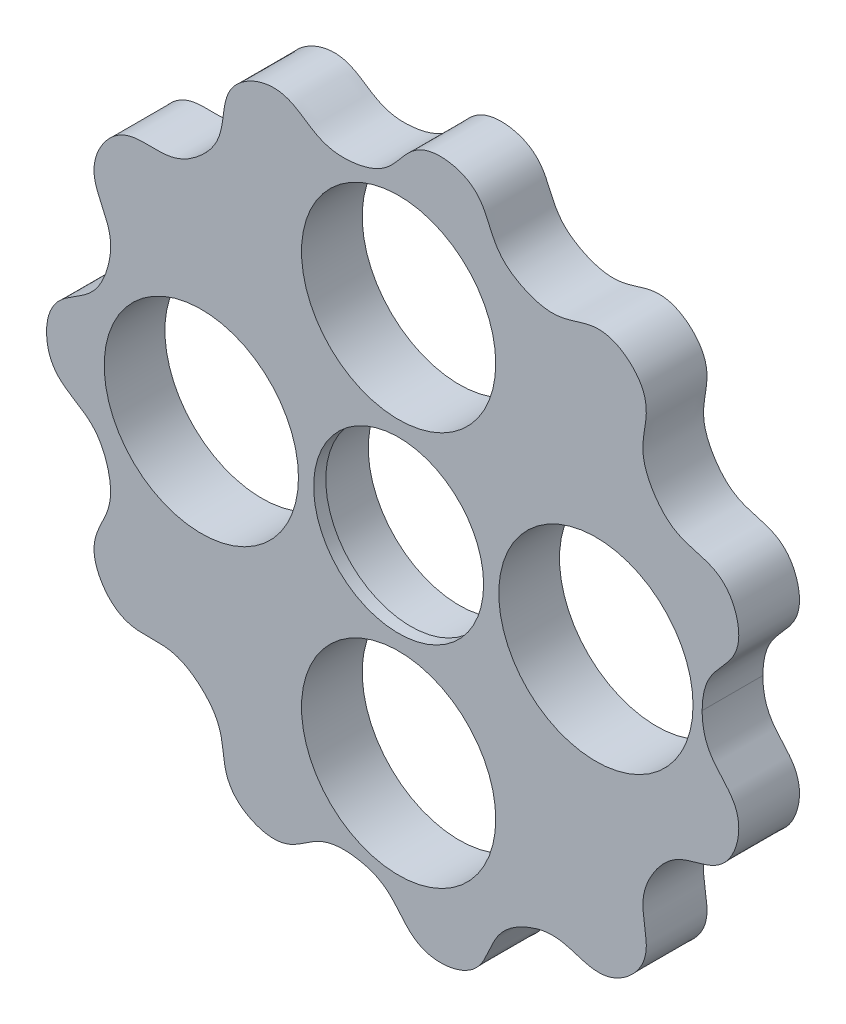
SolidWorks part; units mm, degrees
material "ABS"
ref_plane "Front Plane" through (0, 0, 0) normal (0, 0, 1) x (1, 0, 0)
ref_plane "Top Plane" through (0, 0, 0) normal (0, 1, 0) x (1, 0, 0)
ref_plane "Right Plane" through (0, 0, 0) normal (1, 0, 0) x (0, 0, -1)
sketch "Sketch2" plane through (0, 0, 0) normal (0, 0, 1) x (1, 0, 0)
  line L0 (2, 0) -> (18.25, 0) construction
  line L1 (2, 0) -> (2, 16.25) construction
  line L2 (2, 0) -> (-14.25, 0) construction
  line L3 (2, 0) -> (2, -16.25) construction
  circle A0 centre (2, 0) radius 7.5
  circle A1 centre (18.25, 0) radius 8
  circle A2 centre (2, 16.25) radius 8
  circle A3 centre (-14.25, 0) radius 8
  circle A4 centre (2, -16.25) radius 8
  spline S0 degree 5 poles (-27, 0) (-27, -0.3812) (-26.9508, -0.8895) (-26.8075, -1.5014) (-26.5012, -2.1537) (-25.894, -2.8636) (-25.332, -3.3018) (-24.7079, -3.6802) (-23.8757, -4.1833) (-23.0502, -4.8561) (-22.3649, -5.8294) (-21.9277, -7.0292) (-21.6821, -8.2633) (-21.7019, -9.3372) (-21.9494, -10.2468) (-22.241, -10.9072) (-22.5702, -11.5609) (-22.8569, -12.2233) (-23.03, -12.7873) (-23.1411, -13.5971) (-23.0145, -14.5495) (-22.5942, -15.4953) (-21.9781, -16.3412) (-21.2192, -16.9653) (-20.5887, -17.288) (-19.9177, -17.4897) (-19.208, -17.5545) (-18.4785, -17.5354) (-17.5064, -17.5087) (-16.4482, -17.6284) (-15.3454, -18.0767) (-14.3289, -18.8496) (-13.4551, -19.755) (-12.8912, -20.6692) (-12.6077, -21.5682) (-12.496, -22.2814) (-12.4195, -23.0093) (-12.3025, -23.7215) (-12.1433, -24.2896) (-11.7989, -25.0309) (-11.1775, -25.7637) (-10.3126, -26.3321) (-9.3369, -26.7106) (-8.3611, -26.8254) (-7.6562, -26.7559) (-6.9827, -26.5629) (-6.3507, -26.2337) (-5.7472, -25.8232) (-4.9439, -25.2752) (-3.989, -24.8038) (-2.8189, -24.5847) (-1.5459, -24.6854) (-0.3213, -24.9747) (0.6473, -25.4388) (1.3719, -26.0418) (1.8515, -26.5814) (2.3093, -27.1524) (2.7928, -27.6883) (3.2339, -28.0801) (3.9243, -28.5176) (4.8433, -28.7981) (5.8782, -28.8087) (6.9036, -28.5996) (7.7866, -28.1686) (8.342, -27.7291) (8.8042, -27.2025) (9.158, -26.5839) (9.4437, -25.9123) (9.8233, -25.017) (10.3717, -24.1041) (11.2376, -23.2873) (12.3629, -22.6837) (13.5495, -22.265) (14.6153, -22.1318) (15.5508, -22.2474) (16.2461, -22.442) (16.9399, -22.6749) (17.6364, -22.8643) (18.2193, -22.9554) (19.0366, -22.9502) (19.9613, -22.6893) (20.8377, -22.1387) (21.5873, -21.4084) (22.0971, -20.5685) (22.3267, -19.8984) (22.4309, -19.2056) (22.394, -18.4939) (22.2713, -17.7745) (22.1066, -16.8161) (22.0744, -15.7516) (22.3612, -14.5963) (22.9816, -13.4802) (23.7534, -12.4864) (24.578, -11.7981) (25.4275, -11.3895) (26.1176, -11.1774) (26.8272, -10.9982) (27.5155, -10.781) (28.0551, -10.5425) (28.7399, -10.0962) (29.3768, -9.3768) (29.8163, -8.4398) (30.0522, -7.4202) (30.0269, -6.438) (29.8578, -5.7502) (29.5709, -5.111) (29.1551, -4.5322) (28.6629, -3.9934) (28.0062, -3.2762) (27.4036, -2.3981) (27.1353, -1.6092) (27.026, -0.874) (27, -0.2497) (27, 0) knots 0.5 0.5 0.5 0.5 0.5 0.5 0.509091 0.512121 0.515152 0.518182 0.524242 0.527273 0.530303 0.539394 0.545455 0.554545 0.557576 0.560606 0.566667 0.569697 0.572727 0.575758 0.578788 0.581818 0.590909 0.59697 0.6 0.60303 0.606061 0.609091 0.615152 0.618182 0.621212 0.630303 0.636364 0.645455 0.648485 0.651515 0.657576 0.660606 0.663636 0.666667 0.669697 0.672727 0.681818 0.687879 0.690909 0.693939 0.69697 0.7 0.706061 0.709091 0.712121 0.721212 0.727273 0.736364 0.739394 0.742424 0.748485 0.751515 0.754545 0.757576 0.760606 0.763636 0.772727 0.778788 0.781818 0.784848 0.787879 0.790909 0.79697 0.8 0.80303 0.812121 0.818182 0.827273 0.830303 0.833333 0.839394 0.842424 0.845455 0.848485 0.851515 0.854545 0.863636 0.869697 0.872727 0.875758 0.878788 0.881818 0.887879 0.890909 0.893939 0.90303 0.909091 0.918182 0.921212 0.924242 0.930303 0.933333 0.936364 0.939394 0.942424 0.945455 0.954545 0.960606 0.963636 0.966667 0.969697 0.972727 0.978788 0.981818 0.984848 0.993939 1 1 1 1 1 1 weights 1 1 1 1 1 1 1 1 1 1 1 1 1 1 1 1 1 1 1 1 1 1 1 1 1 1 1 1 1 1 1 1 1 1 1 1 1 1 1 1 1 1 1 1 1 1 1 1 1 1 1 1 1 1 1 1 1 1 1 1 1 1 1 1 1 1 1 1 1 1 1 1 1 1 1 1 1 1 1 1 1 1 1 1 1 1 1 1 1 1 1 1 1 1 1 1 1 1 1 1 1 1 1 1 1 1 1 1 1 1 1 1 1 1
  spline S1 degree 5 poles (27, 0) (27, 0.4994) (27.052, 1.1238) (27.2159, 1.965) (27.6332, 2.8086) (28.332, 3.6359) (28.8321, 4.1703) (29.2937, 4.7252) (29.6187, 5.2175) (29.9535, 5.9632) (30.1003, 6.9128) (29.9635, 7.9386) (29.6107, 8.9238) (29.0583, 9.7365) (28.5443, 10.2237) (27.9573, 10.6063) (27.2946, 10.8684) (26.5892, 11.0556) (25.649, 11.3039) (24.6674, 11.7169) (23.7356, 12.4577) (22.9781, 13.4857) (22.3947, 14.6006) (22.1112, 15.6366) (22.0924, 16.579) (22.1862, 17.2949) (22.3179, 18.0148) (22.4063, 18.7311) (22.4135, 19.3211) (22.292, 20.1294) (21.9021, 21.0075) (21.2325, 21.7966) (20.403, 22.4347) (19.499, 22.8197) (18.8031, 22.9517) (18.1025, 22.9562) (17.4033, 22.8184) (16.7086, 22.5945) (15.7835, 22.2951) (14.7344, 22.1118) (13.55, 22.2312) (12.357, 22.6865) (11.2635, 23.309) (10.4649, 24.0273) (9.9395, 24.81) (9.6314, 25.4629) (9.353, 26.1397) (9.0401, 26.7901) (8.7272, 27.2903) (8.188, 27.9046) (7.3852, 28.4326) (6.3952, 28.7343) (5.3525, 28.8226) (4.3838, 28.6578) (3.727, 28.3926) (3.1352, 28.0176) (2.6215, 27.5237) (2.1582, 26.9598) (1.5418, 26.2077) (0.7583, 25.4863) (-0.3026, 24.9465) (-1.5524, 24.6845) (-2.8089, 24.617) (-3.869, 24.7895) (-4.7341, 25.1639) (-5.3464, 25.5466) (-5.9465, 25.9654) (-6.5614, 26.3434) (-7.095, 26.5951) (-7.8807, 26.8203) (-8.8415, 26.8305) (-9.8374, 26.5491) (-10.7624, 26.0596) (-11.4882, 25.3973) (-11.8973, 24.8191) (-12.1925, 24.1837) (-12.3576, 23.4904) (-12.4425, 22.7656) (-12.5545, 21.7996) (-12.8235, 20.7692) (-13.4242, 19.7415) (-14.3339, 18.8453) (-15.3545, 18.1093) (-16.3395, 17.6812) (-17.2697, 17.5285) (-17.9917, 17.5194) (-18.723, 17.5473) (-19.4446, 17.5329) (-20.0296, 17.4561) (-20.8123, 17.2208) (-21.6261, 16.7099) (-22.3118, 15.9347) (-22.8253, 15.0229) (-23.0778, 14.0733) (-23.1094, 13.3657) (-23.0141, 12.6716) (-22.7782, 11.9991) (-22.4578, 11.3434) (-22.0297, 10.4702) (-21.699, 9.4579) (-21.6487, 8.2686) (-21.9295, 7.0229) (-22.3901, 5.852) (-22.9874, 4.9593) (-23.6873, 4.3279) (-24.2898, 3.9299) (-24.9201, 3.5581) (-25.5193, 3.1558) (-25.9699, 2.7749) (-26.5012, 2.1537) (-26.8075, 1.5014) (-26.9508, 0.8895) (-27, 0.3812) (-27, 0) knots 0 0 0 0 0 0 0.012121 0.015152 0.021212 0.024242 0.027273 0.030303 0.033333 0.036364 0.045455 0.051515 0.054545 0.057576 0.060606 0.063636 0.069697 0.072727 0.075758 0.084848 0.090909 0.1 0.10303 0.106061 0.112121 0.115152 0.118182 0.121212 0.124242 0.127273 0.136364 0.142424 0.145455 0.148485 0.151515 0.154545 0.160606 0.163636 0.166667 0.175758 0.181818 0.190909 0.193939 0.19697 0.20303 0.206061 0.209091 0.212121 0.215152 0.218182 0.227273 0.233333 0.236364 0.239394 0.242424 0.245455 0.251515 0.254545 0.257576 0.266667 0.272727 0.281818 0.284848 0.287879 0.293939 0.29697 0.3 0.30303 0.306061 0.309091 0.318182 0.324242 0.327273 0.330303 0.333333 0.336364 0.342424 0.345455 0.348485 0.357576 0.363636 0.372727 0.375758 0.378788 0.384848 0.387879 0.390909 0.393939 0.39697 0.4 0.409091 0.415152 0.418182 0.421212 0.424242 0.427273 0.433333 0.436364 0.439394 0.448485 0.454545 0.463636 0.466667 0.469697 0.475758 0.478788 0.481818 0.484848 0.487879 0.490909 0.5 0.5 0.5 0.5 0.5 0.5 weights 1 1 1 1 1 1 1 1 1 1 1 1 1 1 1 1 1 1 1 1 1 1 1 1 1 1 1 1 1 1 1 1 1 1 1 1 1 1 1 1 1 1 1 1 1 1 1 1 1 1 1 1 1 1 1 1 1 1 1 1 1 1 1 1 1 1 1 1 1 1 1 1 1 1 1 1 1 1 1 1 1 1 1 1 1 1 1 1 1 1 1 1 1 1 1 1 1 1 1 1 1 1 1 1 1 1 1 1 1 1 1 1 1 1
  point P3 (0, 0)
  point P4 (2, 0)
extrude "Boss-Extrude2" add sketch "Sketch2" along normal blind 5
sketch "Sketch3" plane through (0, 0, 5) normal (0, 0, 1) x (1, 0, 0)
  circle A0 centre (2, 0) radius 7.5
  circle A1 centre (2, 0) radius 7
  dimension "D1" = 15
  dimension "D2" = 14
extrude "Boss-Extrude3" add sketch "Sketch3" against normal blind 1
